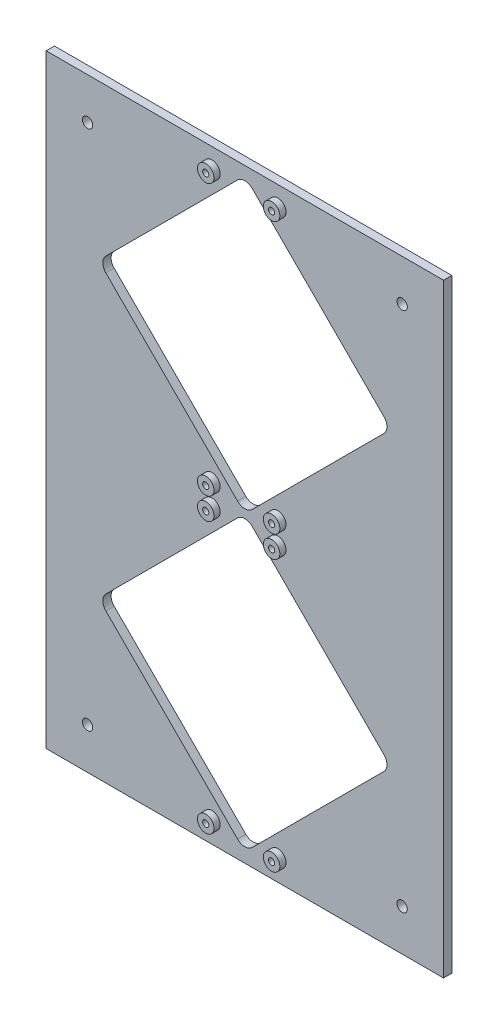
SolidWorks part; units mm, degrees
ref_plane "Plan de face" through (0, 0, 0) normal (0, 0, 1) x (1, 0, 0)
ref_plane "Plan de dessus" through (0, 0, 0) normal (0, 1, 0) x (1, 0, 0)
ref_plane "Plan de droite" through (0, 0, 0) normal (1, 0, 0) x (0, 0, -1)
sketch "Esquisse1" plane through (0, 0, 0) normal (0, 0, 1) x (1, 0, 0)
  line L1 (-18.6784, 280.4189) -> (173.3216, 280.4189)
  line L2 (-18.6784, 280.4189) -> (-18.6784, -11.5811)
  line L3 (-18.6784, -11.5811) -> (173.3216, -11.5811)
  line L4 (173.3216, 280.4189) -> (173.3216, -11.5811)
  dimension "D1" = 192
  dimension "D2" = 292
extrude "Boss.-Extru.1" add sketch "Esquisse1" along normal blind 4 contours L2 L1 L4 L3
sketch "Esquisse4" plane through (0, 0, 4) normal (0, 0, 1) x (1, 0, 0)
  line L0 (-18.6784, 205.4082) -> (173.3216, 205.4082) construction
  line L3 (-18.6784, 280.4189) -> (173.3216, 280.4189) construction
  line L4 (77.3216, 280.4189) -> (77.3216, -11.5811) construction
  line L5 (-18.6784, -11.5811) -> (173.3216, -11.5811) construction
  line L6 (-18.6784, 280.4189) -> (-18.6784, -11.5811) construction
  line L7 (173.3216, 280.4189) -> (173.3216, -11.5811) construction
  line L8 (77.3216, 276.1189) -> (148.0322, 205.4082)
  line L9 (77.3216, 276.1189) -> (6.6109, 205.4082)
  line L10 (148.0322, 205.4082) -> (77.3216, 134.6975)
  line L11 (6.6109, 205.4082) -> (77.3216, 134.6975)
  line L12 (77.3216, 276.1189) -> (77.3216, 134.6975) construction
  line L13 (148.0322, 205.4082) -> (6.6109, 205.4082) construction
  line L14 (77.3216, 276.1189) -> (77.3216, 280.4189)
  point P13 (77.3216, 205.4082)
  dimension "D1" = 100
  dimension "D2" = 100
  dimension "D3" = 4.3
extrude "Enlèv. mat.-Extru.17" cut sketch "Esquisse4" against normal through all contours L9 L11 L10 L8
pattern_linear "Répétition linéaire2" count 2 spacing 141.43 along (0, -1, 0) of "Enlèv. mat.-Extru.17"
sketch "Esquisse5" plane through (0, 0, 4) normal (0, 0, 1) x (1, 0, 0)
  line L0 (77.3216, 276.1189) -> (66.715, 265.5123) construction
  line L1 (77.3216, 276.1189) -> (6.6109, 205.4082) construction
  line L2 (66.715, 265.5123) -> (61.4117, 270.8156) construction
  line L3 (77.3216, 276.1189) -> (87.9282, 265.5123) construction
  line L4 (77.3216, 276.1189) -> (148.0322, 205.4082) construction
  line L5 (87.9282, 265.5123) -> (93.2315, 270.8156) construction
  circle A0 centre (61.4117, 270.8156) radius 4
  circle A1 centre (93.2315, 270.8156) radius 4
  dimension "D1" = 15
  dimension "D2" = 7.5
  dimension "D3" = 15
  dimension "D4" = 7.5
extrude "Boss.-Extru.2" add sketch "Esquisse5" along normal blind 3
sketch "Esquisse6" plane through (0, 0, 7) normal (0, 0, 1) x (1, 0, 0)
  circle A2 centre (61.4117, 270.8156) radius 1.5
  circle A3 centre (61.4117, 270.8156) radius 1.5
  circle A5 centre (93.2315, 270.8156) radius 1.5
  circle A6 centre (93.2315, 270.8156) radius 1.5
  dimension "D1" = 2.5
  dimension "D2" = 2.5
extrude "Enlèv. mat.-Extru.18" cut sketch "Esquisse6" against normal blind 6 contours A3
sketch "Esquisse7" plane through (0, 0, 7) normal (0, 0, 1) x (1, 0, 0)
  circle A2 centre (93.2315, 270.8156) radius 1.5
  circle A3 centre (93.2315, 270.8156) radius 1.5
  dimension "D1" = 2.5
extrude "Enlèv. mat.-Extru.19" cut sketch "Esquisse7" against normal blind 6 contours A3
sketch "Esquisse9" plane through (0, 0, 4) normal (0, 0, 1) x (1, 0, 0)
  line L0 (77.3216, 134.6889) -> (87.9282, 124.0823) construction
  line L1 (77.3216, 134.6889) -> (148.0322, 63.9782) construction
  line L2 (87.9282, 124.0823) -> (93.2315, 129.3856) construction
  circle A0 centre (93.2315, 129.3856) radius 4
  dimension "D1" = 7.5
  dimension "D2" = 15
pattern_linear "Répétition linéaire5" count 2 spacing 130.815 along (0, -1, 0) of "Boss.-Extru.2", "Enlèv. mat.-Extru.18"
sketch "Esquisse10" plane through (0, 0, 7) normal (0, 0, 1) x (1, 0, 0)
  circle A2 centre (93.2315, 140.0006) radius 1.5
  circle A3 centre (93.2315, 140.0006) radius 1.5
  dimension "D1" = 2.5
extrude "Enlèv. mat.-Extru.20" cut sketch "Esquisse10" against normal blind 6
extrude "Boss.-Extru.3" add sketch "Esquisse9" along normal blind 3
sketch "Esquisse11" plane through (0, 0, 7) normal (0, 0, 1) x (1, 0, 0)
  circle A2 centre (93.2315, 129.3856) radius 1.5
  circle A3 centre (93.2315, 129.3856) radius 1.5
  dimension "D1" = 2.5
extrude "Enlèv. mat.-Extru.21" cut sketch "Esquisse11" against normal blind 6
pattern_linear "Répétition linéaire6" count 2 spacing 31.82 along (-1, 0, 0) of "Enlèv. mat.-Extru.21", "Boss.-Extru.3"
pattern_linear "Répétition linéaire7" count 2 spacing 130.815 along (0, -1, 0) of "Répétition linéaire6", "Boss.-Extru.3", "Enlèv. mat.-Extru.21"
sketch "Esquisse14" plane through (0, 0, 4) normal (0, 0, 1) x (1, 0, 0)
  line L0 (-18.6784, 280.4189) -> (-18.6784, -11.5811) construction
  line L1 (-18.6784, 280.4189) -> (173.3216, 280.4189) construction
  line L2 (173.3216, 280.4189) -> (173.3216, -11.5811) construction
  line L3 (-18.6784, -11.5811) -> (173.3216, -11.5811) construction
  circle A0 centre (1.3216, 8.4189) radius 2.5
  circle A1 centre (153.3216, 8.4189) radius 2.5
  circle A2 centre (153.3216, 260.4189) radius 2.5
  circle A3 centre (1.3216, 260.4189) radius 2.5
  point P8 (0, 0)
  dimension "D1" = 20
  dimension "D3" = 20
  dimension "D4" = 20
  dimension "D5" = 20
  dimension "D6" = 20
  dimension "D7" = 20
  dimension "D8" = 20
  dimension "D2" = 20
extrude "Enlèv. mat.-Extru.22" cut sketch "Esquisse14" against normal through all
fillet "Congé2" radius 5 8 edges at (6.6109, 205.4082, 2) (77.3216, 276.1189, 2) (148.0322, 205.4082, 2) (77.3216, 134.6975, 2) (6.6109, 63.9782, 2) (77.3216, 134.6889, 2) (148.0322, 63.9782, 2) (77.3216, -6.7325, 2)
